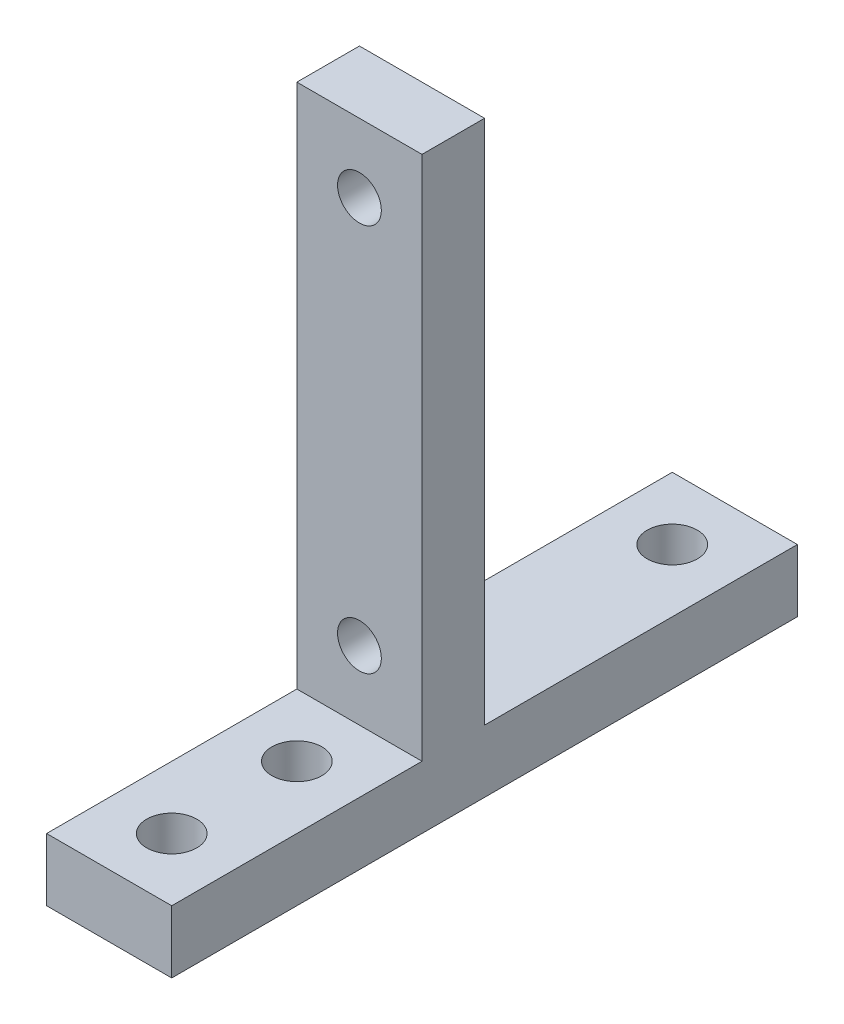
SolidWorks part; units mm, degrees
material "ABS"
ref_plane "Plano frontal" through (0, 0, 0) normal (0, 0, 1) x (1, 0, 0)
ref_plane "Plano superior" through (0, 0, 0) normal (0, 1, 0) x (1, 0, 0)
ref_plane "Plano direito" through (0, 0, 0) normal (1, 0, 0) x (0, 0, -1)
sketch "Esboço1" plane through (0, 0, 0) normal (0, 0, 1) x (1, 0, 0)
  line L0 (5, -21) -> (5, 21)
  line L1 (-5, 21) -> (5, 21)
  line L2 (-5, 21) -> (-5, -21)
  line L3 (-5, -21) -> (5, -21)
  line L11 (0, 15.5) -> (0, -15.5) construction
  circle A1 centre (0, 15.5) radius 1.75
  circle A4 centre (0, -15.5) radius 1.75
  point P0 (0, 0)
  point P1 (0, 21)
  point P4 (0, 0)
  point P6 (-5, 20.7379)
  point P7 (5, 0)
  dimension "D2" = 31
  dimension "D4" = 10
  dimension "D1" = 3.5
  dimension "D3" = 42
extrude "Ressalto-extrusão1" add sketch "Esboço1" along normal blind 5
sketch "Esboço2" plane through (0, -21, 0) normal (0, -1, 0) x (1, 0, 0)
  line L0 (-5, 5) -> (-5, 0) construction
  line L1 (-5, 25) -> (5, 25)
  line L2 (-5, 25) -> (-5, -25)
  line L3 (-5, -25) -> (5, -25)
  line L4 (5, 25) -> (5, -25)
  line L5 (5, 5) -> (5, 0) construction
  line L6 (0, 20) -> (0, -20) construction
  line L7 (-5, 5) -> (5, 5) construction
  circle A0 centre (0, 20) radius 2
  circle A1 centre (0, -20) radius 2
  circle A2 centre (0, 10) radius 2
  point P14 (0, 8.786)
  point P15 (0, 25)
  dimension "D4" = 10
  dimension "D5" = 4
  dimension "D1" = 40
  dimension "D2" = 5
  dimension "D3" = 5
  dimension "D6" = 5
extrude "Ressalto-extrusão2" add sketch "Esboço2" along normal blind 5
